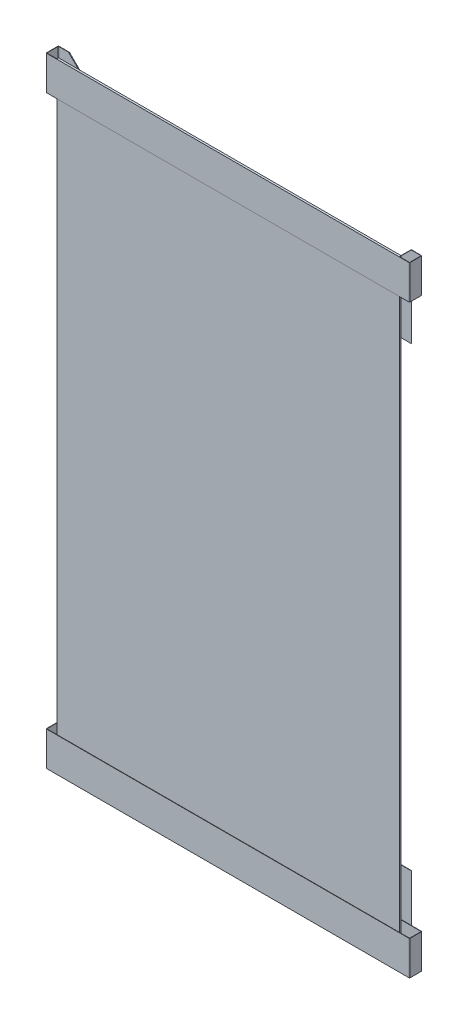
SolidWorks part; units mm, degrees
ref_plane "Front Plane" through (0, 0, 0) normal (0, 0, 1) x (1, 0, 0)
ref_plane "Top Plane" through (0, 0, 0) normal (0, 1, 0) x (1, 0, 0)
ref_plane "Right Plane" through (0, 0, 0) normal (1, 0, 0) x (0, 0, -1)
ref_plane "Plane1" through (0, 0, 0.25) normal (0, 0, 1) x (1, 0, 0)
sketch "Sketch1" plane through (0, 0, 0.25) normal (0, 0, 1) x (1, 0, 0)
  line L0 (25, -42.75) -> (25, 45.25)
  line L1 (25, 45.25) -> (-25, 45.25)
  line L2 (-25, 45.25) -> (-25, -42.75)
  line L3 (-25, -42.75) -> (25, -42.75)
  dimension "D1" = 50
  dimension "D2" = 88
  dimension "D3" = 25
  dimension "D4" = 42.75
extrude "Boss-Extrude1" add sketch "Sketch1" against normal blind 0.25
ref_plane "Plane3" through (0, -45.25, 0) normal (0, -1, 0) x (-1, 0, 0)
sketch "Sketch4" plane through (0, -45.25, 0) normal (0, -1, 0) x (-1, 0, 0)
  line L1 (-26.45, -0.25) -> (26.45, -0.25)
  line L3 (-26.5, -0.3) -> (26.5, -0.3)
  line L4 (25, 0) -> (25, -0.25) construction
  line L5 (0, 0) -> (0, 2.5169) construction
  line L6 (25, -0.25) -> (-25, -0.25) construction
  line L7 (-20, 1.5) -> (-20, 1.45)
  line L8 (26.5, -0.2) -> (26.5, 1.4)
  line L9 (-26.45, 1.45) -> (-20, 1.45)
  line L10 (26.55, -0.25) -> (26.55, 1.45)
  line L11 (26.5, 1.5) -> (20, 1.5)
  line L12 (-26.5, 1.5) -> (-20, 1.5)
  line L13 (26.45, 1.45) -> (20, 1.45)
  line L14 (20, 1.5) -> (20, 1.45)
  line L15 (-26.55, -0.25) -> (-26.55, 1.45)
  line L16 (-26.5, -0.2) -> (-26.5, 1.4)
  arc A0 (26.5, 1.5) -> (26.55, 1.45) centre (26.5, 1.45) cw
  arc A1 (26.5, 1.4) -> (26.45, 1.45) centre (26.45, 1.4) ccw
  arc A2 (26.5, -0.3) -> (26.55, -0.25) centre (26.5, -0.25) ccw
  arc A3 (26.45, -0.25) -> (26.5, -0.2) centre (26.45, -0.2) ccw
  arc A4 (-26.45, -0.25) -> (-26.5, -0.2) centre (-26.45, -0.2) cw
  arc A5 (-26.5, -0.3) -> (-26.55, -0.25) centre (-26.5, -0.25) cw
  arc A6 (-26.5, 1.4) -> (-26.45, 1.45) centre (-26.45, 1.4) cw
  arc A7 (-26.5, 1.5) -> (-26.55, 1.45) centre (-26.5, 1.45) ccw
  dimension "D1" = 0.05
  dimension "D2" = 6.5
  dimension "D4" = 0.05
  dimension "D5" = 0.05
  dimension "D6" = 1.7
  dimension "D7" = 1.5
extrude "Boss-Extrude2" add sketch "Sketch4" against normal blind 5
sketch "Sketch5" plane through (0, 0, -1.5) normal (0, 0, -1) x (-1, 0, 0)
  line L0 (0, 0) -> (0, -53.2903) construction
  line L1 (20, -45.25) -> (25, -45.25)
  line L2 (20, -45.25) -> (20, -33.35)
  line L3 (20, -33.35) -> (25, -33.35)
  line L4 (25, -45.25) -> (25, -33.35)
  line L5 (-25, -45.25) -> (-25, -33.35)
  line L6 (-20, -33.35) -> (-25, -33.35)
  line L7 (-20, -45.25) -> (-20, -33.35)
  line L8 (-20, -45.25) -> (-25, -45.25)
  dimension "D1" = 5
  dimension "D2" = 11.9
extrude "Boss-Extrude3" add sketch "Sketch5" along normal blind 0.05
sketch "Sketch6" plane through (0, 0, -1.55) normal (0, 0, -1) x (-1, 0, 0)
  line L1 (20, -45.25) -> (25, -45.25)
  line L2 (20, -45.25) -> (20, -40.2549)
  line L3 (0, 0) -> (0, -53.2763) construction
  line L4 (-20, -40.2549) -> (-25, -45.25)
  line L5 (20, -40.2549) -> (25, -45.25)
  line L6 (-20, -45.25) -> (-20, -40.2549)
  line L7 (-20, -45.25) -> (-25, -45.25)
  dimension "D1" = 4.9951
  dimension "D2" = 5
extrude "Cut-Extrude1" cut sketch "Sketch6" against normal blind 0.2
fillet "Fillet1" radius 0.04 4 edges at (-22.5, -42.7525, -1.45) (-22.5, -42.7525, -1.55) (22.5, -42.7525, -1.55) (22.5, -42.7525, -1.45)
sketch "Sketch7" plane through (0, 0, 0.25) normal (0, 0, 1) x (1, 0, 0)
  line L0 (-25, 0) -> (25, 0) construction
  line L1 (-25, 45.25) -> (-25, -40.25) construction
  line L2 (25, -40.25) -> (25, 45.25) construction
  dimension "D1" = 0
ref_plane "Plane4" through (0, 0, 0) normal (0, -1, 0) x (-1, 0, 0)
mirror "Mirror1" about plane through (0, 0, 0) normal (0, -1, 0) of "Boss-Extrude2", "Boss-Extrude3", "Cut-Extrude1", "Fillet1"
